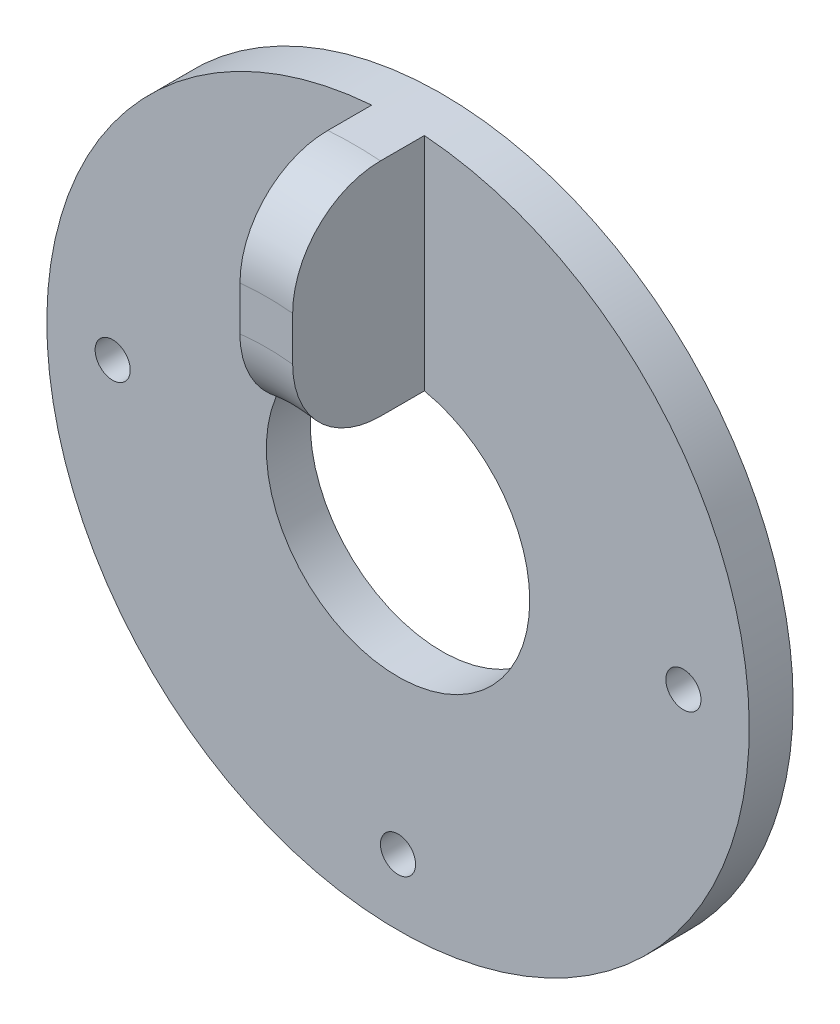
SolidWorks part; units mm, degrees
ref_plane "前视基准面" through (0, 0, 0) normal (0, 0, 1) x (1, 0, 0)
ref_plane "上视基准面" through (0, 0, 0) normal (0, 1, 0) x (1, 0, 0)
ref_plane "右视基准面" through (0, 0, 0) normal (1, 0, 0) x (0, 0, -1)
other "Configuration Table"
sketch "草图1" plane through (0, 0, 0) normal (0, 0, 1) x (1, 0, 0)
  circle A0 centre (0, 0) radius 40
  dimension "D1" = 80
extrude "凸台-拉伸1" add sketch "草图1" along normal blind 5
sketch "草图3" plane through (0, 0, 5) normal (0, 0, 1) x (1, 0, 0)
  circle A0 centre (0, 0) radius 15
  dimension "D1" = 30
extrude "切除-拉伸1" cut sketch "草图3" against normal blind 10
sketch "草图4" plane through (0, 0, 5) normal (0, 0, 1) x (1, 0, 0)
  circle A0 centre (0, 0) radius 32.5 construction
  circle A2 centre (0, -32.5) radius 2
  circle A3 centre (32.5, 0) radius 2
  circle A4 centre (-32.5, 0) radius 2
  dimension "D1" = 65
  dimension "D2" = 4
extrude "切除-拉伸2" cut sketch "草图4" against normal blind 10
sketch "草图5" plane through (0, 0, 5) normal (0, 0, 1) x (1, 0, 0)
  line L2 (-3, 39.8873) -> (-3, 14.6969)
  line L4 (3, 39.8873) -> (3, 14.6969)
  circle A0 centre (0, 0) radius 15 construction
  arc A1 (3, 14.6969) -> (-3, 14.6969) centre (0, 0) ccw
  circle A2 centre (0, 0) radius 40 construction
  arc A3 (3, 39.8873) -> (-3, 39.8873) centre (0, 0) ccw
  dimension "D1" = 6
  dimension "D2" = 3
extrude "凸台-拉伸2" add sketch "草图5" along normal blind 15
fillet "圆角1" radius 10 2 edges at (0, 15, 20) (0, 40, 20)
